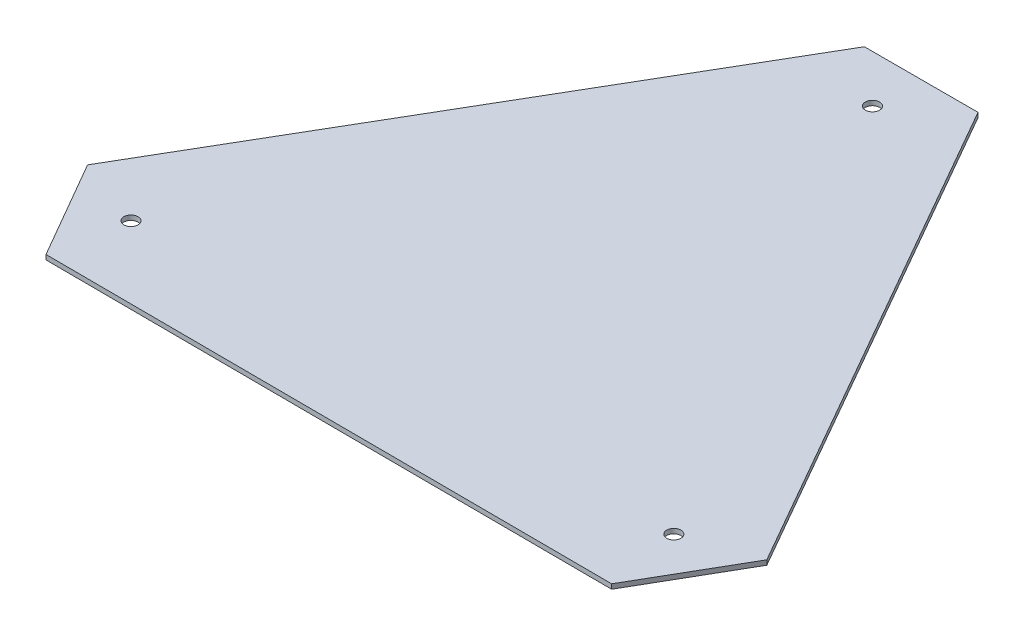
SolidWorks part; units mm, degrees
material "0.6010 (EN-GJL-100)"
ref_plane "Alzado" through (0, 0, 0) normal (0, 0, 1) x (1, 0, 0)
ref_plane "Planta" through (0, 0, 0) normal (0, 1, 0) x (1, 0, 0)
ref_plane "Vista lateral" through (0, 0, 0) normal (1, 0, 0) x (0, 0, -1)
sketch "Croquis1" plane through (0, 0, 0) normal (0, 1, 0) x (1, 0, 0)
  line L0 (-11.7055, 76.2096) -> (12.2945, 76.2096)
  line L1 (-11.7055, 76.2096) -> (-72.1467, -27.4575)
  line L2 (-60.1467, -48.2421) -> (59.8522, -48.7521)
  line L3 (71.8522, -27.9675) -> (12.2945, 76.2096)
  line L4 (71.8522, -27.9675) -> (59.8522, -48.7521)
  line L5 (-60.1467, -48.2421) -> (-72.1467, -27.4575)
  circle A0 centre (0, 0) radius 48.4973 construction
  circle A1 centre (0, 66.2096) radius 1.5
  circle A2 centre (57.3392, -33.1048) radius 1.5
  circle A3 centre (-57.3392, -33.1048) radius 1.5
  point P14 (0, 0)
  point P18 (0, 0)
  dimension "D4" = 3
  dimension "D1" = 24
  dimension "D3" = 120
  dimension "D5" = 10
  dimension "D2" = 3
  dimension "D6" = 3
extrude "Saliente-Extruir1" add sketch "Croquis1" along normal blind 1
